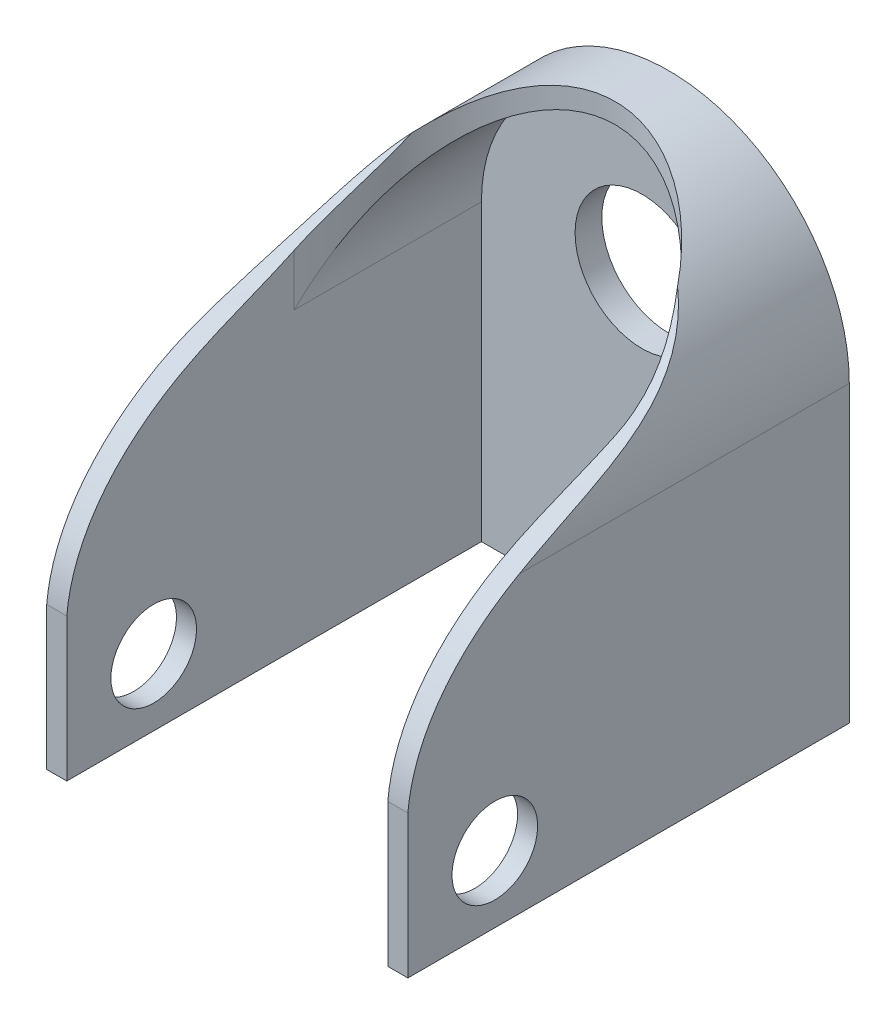
SolidWorks part; units mm, degrees
ref_plane "Front Plane" through (0, 0, 0) normal (0, 0, 1) x (1, 0, 0)
ref_plane "Top Plane" through (0, 0, 0) normal (0, 1, 0) x (1, 0, 0)
ref_plane "Right Plane" through (0, 0, 0) normal (1, 0, 0) x (0, 0, -1)
sketch "Sketch1" plane through (0, 0, 0) normal (0, 0, 1) x (1, 0, 0)
  line L0 (0, 0) -> (0, 22)
  line L1 (27, 22) -> (27, 0)
  line L2 (27, 0) -> (0, 0)
  arc A0 (0, 22) -> (27, 22) centre (13.5, 22) cw
  dimension "D1" = 22
  dimension "D2" = 27
extrude "Boss-Extrude1" add sketch "Sketch1" along normal blind 2
sketch "Sketch2" plane through (0, 0, 2) normal (0, 0, 1) x (1, 0, 0)
  line L0 (27, 0) -> (27, 22) construction
  line L1 (0, 22) -> (0, 0) construction
  line L2 (27, 0) -> (27, 22)
  line L3 (0, 22) -> (0, 0)
  line L6 (25.5, 1.5) -> (25.5, 22)
  line L7 (1.5, 22) -> (1.5, 1.5)
  line L9 (0, 0) -> (27, 0) construction
  line L10 (1.5, 1.5) -> (25.5, 1.5) construction
  line L11 (1.5, 1.5) -> (1.5, 0)
  line L12 (0, 0) -> (27, 0) construction
  line L13 (1.5, 0) -> (0, 0)
  line L14 (25.5, 1.5) -> (25.5, 0)
  line L15 (25.5, 0) -> (27, 0)
  arc A0 (27, 22) -> (0, 22) centre (13.5, 22) ccw construction
  arc A1 (27, 22) -> (0, 22) centre (13.5, 22) ccw
  arc A2 (25.5, 22) -> (1.5, 22) centre (13.5, 22) ccw
  dimension "D1" = 1.5
extrude "Boss-Extrude2" add sketch "Sketch2" along normal blind 31
sketch "Sketch3" plane through (0, 0, 0) normal (0, 1, 0) x (1, 0, 0)
  line L0 (1.5, -33) -> (1.5, -16)
  line L1 (0, -33) -> (27, -33) construction
  line L2 (25.5, -16) -> (25.5, -33)
  line L3 (25.5, -33) -> (1.5, -33)
  arc A0 (1.5, -16) -> (25.5, -16) centre (13.5, -16) cw
  point P6 (24.9123, -33)
  point P8 (25.5, -33)
  point P10 (1.5, -33)
  point P12 (13.5, -13.5469)
  dimension "D1" = 17
extrude "Cut-Extrude1" cut sketch "Sketch3" along normal through all
sketch "Sketch4" plane through (0, 0, 0) normal (-1, 0, 0) x (0, 0, 1)
  line L0 (33, 22) -> (33, 0) construction
  line L1 (33, 22) -> (0, 22) construction
  line L2 (9.1173, 31.3636) -> (9.1173, 0)
  line L3 (33, 0) -> (0, 0) construction
  line L4 (9.1173, 0) -> (33, 0)
  line L5 (33, 0) -> (33, 8.3701)
  line L6 (9.1173, 31.3636) -> (33, 31.3636)
  line L7 (33, 31.3636) -> (33, 8.3701)
  spline S0 degree 3 poles (9.1173, 31.3636) (12.9633, 25.7468) (25.1322, 24.3573) (33.5706, 14.5821) (33, 8.3701) knots 0 0 0 0 0.52297 1 1 1 1
  line M8 (33, 22) -> (0, 22)
extrude "Cut-Extrude2" cut sketch "Sketch4" against normal through all contours L6 S0 L7 M8 | S0 L7 M8
sketch "Sketch5" plane through (0, 0, 0) normal (-1, 0, 0) x (0, 0, 1)
  line L0 (33, 0) -> (0, 0) construction
  line L1 (33, 10.6901) -> (33, 0) construction
  circle A0 centre (26.5, 5) radius 3.2
  point P2 (26.5215, 4.727)
  dimension "D1" = 6.4
  dimension "D2" = 5
  dimension "D3" = 6.5
extrude "Cut-Extrude3" cut sketch "Sketch5" against normal through all
sketch "Sketch6" plane through (0, 0, 0) normal (0, 0, -1) x (-1, 0, 0)
  circle A0 centre (-13.5, 23.5) radius 5
  arc A1 (0, 22) -> (-27, 22) centre (-13.5, 22) ccw construction
  point P2 (-13.5, 35.5)
  point P3 (0, 0)
  dimension "D1" = 12
  dimension "D2" = 10
extrude "Cut-Extrude4" cut sketch "Sketch6" against normal through all
